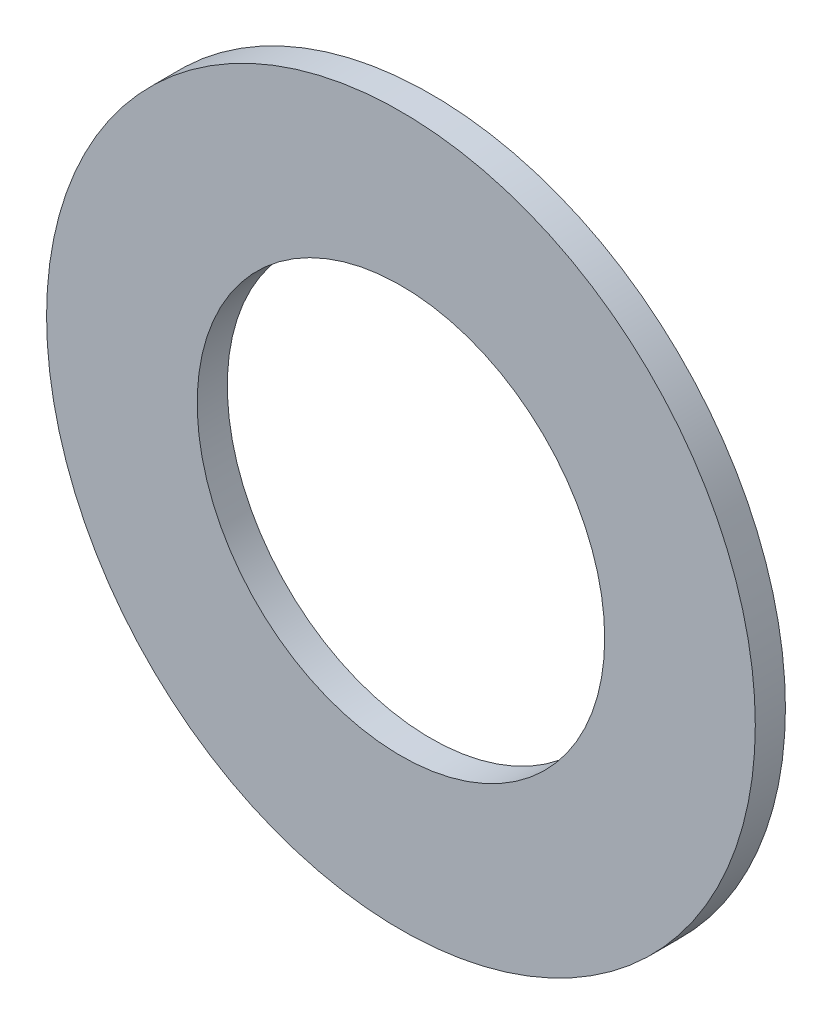
SolidWorks part; units mm, degrees
material "ABS PC"
ref_plane "Front Plane" through (0, 0, 0) normal (0, 0, 1) x (1, 0, 0)
ref_plane "Top Plane" through (0, 0, 0) normal (0, 1, 0) x (1, 0, 0)
ref_plane "Right Plane" through (0, 0, 0) normal (1, 0, 0) x (0, 0, -1)
sketch "Sketch1" plane through (0, 0, 0) normal (0, 0, 1) x (1, 0, 0)
  circle A0 centre (0, 0) radius 20
  circle A1 centre (0, 0) radius 11.5
  dimension "D1" = 40
  dimension "D2" = 23
extrude "Boss-Extrude1" add sketch "Sketch1" along normal blind 1.7
equation "\"smallPulleyTeeth\"= 15"
equation "\"largePulleyTeeth\"= 30"
equation "\"eighthThick\"= 2.9mm"
equation "\"sixteenthThick\" = 1.7mm"
equation "\"quarterThick\"=5.9mm"
equation "\"OD\" = 145mm"
equation "\"puckAngle\" = 60.5deg"
equation "\"puckDiam\" = 76.5mm"
equation "\"axlePress\" = 5.9mm"
equation "\"press\" = 0.2mm"
equation "\"wheelClear\" = 0.3mm"
equation "\"10-32clear\" = 4.5mm"
equation "\"6-32clear\" = 3.3mm"
equation "\"8-32clear\" = 4.0mm"
equation "\"4-40clear\" = 2.55mm"
equation "\"wheelHeight\" = 21mm"
equation "\"wheelWell\" = 62mm"
equation "\"D1@Boss-Extrude1\"=\"sixteenthThick\""
